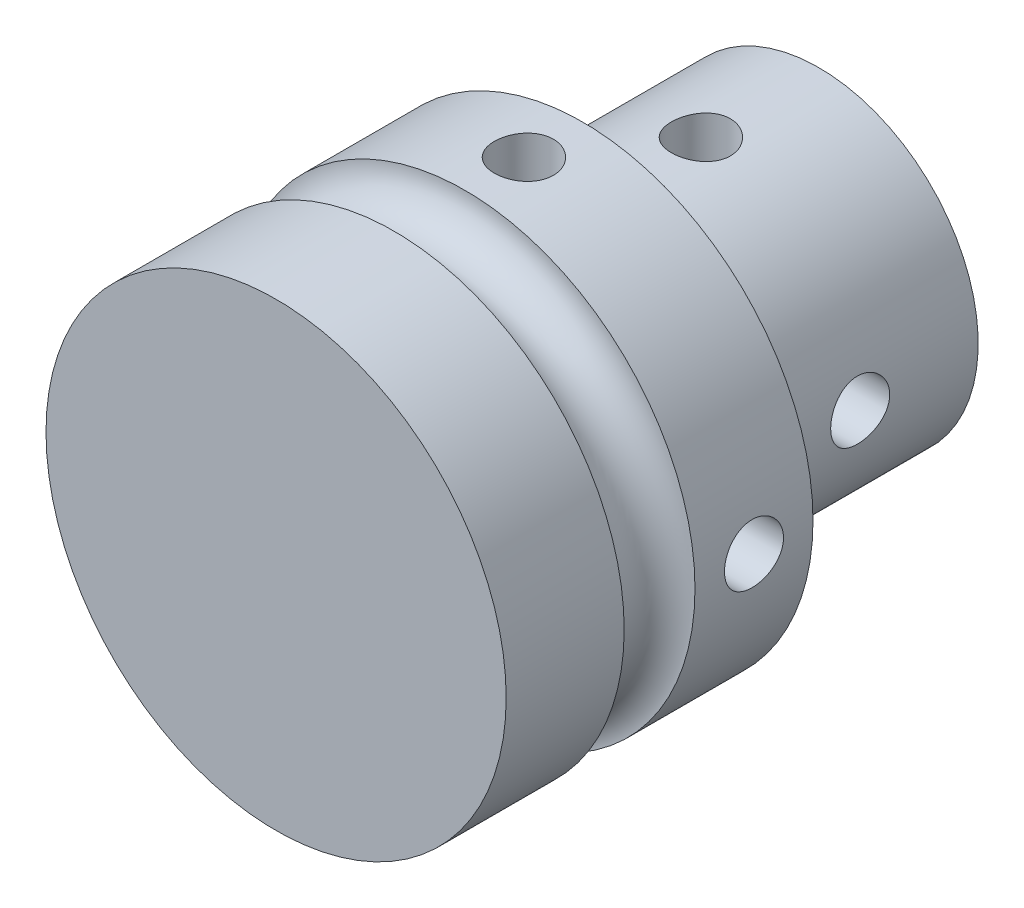
SolidWorks part; units mm, degrees
ref_plane "Plano frontal" through (0, 0, 0) normal (0, 0, 1) x (1, 0, 0)
ref_plane "Plano superior" through (0, 0, 0) normal (0, 1, 0) x (1, 0, 0)
ref_plane "Plano direito" through (0, 0, 0) normal (1, 0, 0) x (0, 0, -1)
sketch "Esboço2" plane through (0, 0, 0) normal (0, 0, 1) x (1, 0, 0)
  circle A0 centre (0, 0) radius 9.75
  dimension "D1" = 19.5
extrude "Ressalto-extrusão1" add sketch "Esboço2" along normal blind 13 contours A0
sketch "Esboço3" plane through (0, 0, 0) normal (0, 1, 0) x (1, 0, 0)
  line L0 (-9.75, -6.5) -> (9.75, -6.5) construction
  line L1 (-9.75, 0) -> (-9.75, -13) construction
  line L2 (9.75, -13) -> (9.75, 0) construction
  line L3 (0, 0) -> (0, -13) construction
  line L4 (-9.75, -13) -> (9.75, -13) construction
  circle A0 centre (9.75, -6.5) radius 1.5
  dimension "D1" = 3
revolve "Corte-Revolução1" cut sketch "Esboço3" angle 360 about L3
sketch "Esboço4" plane through (0, 0, 0) normal (0, 0, -1) x (-1, 0, 0)
  circle A0 centre (0, 0) radius 6.75
  dimension "D1" = 13.5
extrude "Ressalto-extrusão2" add sketch "Esboço4" along normal blind 10
sketch "Esboço11" plane through (0, 0, 0) normal (0, 1, 0) x (1, 0, 0)
  line L0 (0, 0) -> (0, -5) construction
  line L1 (9.75, -5) -> (-9.75, -5) construction
  circle A0 centre (0, -2.5) radius 1.5
  dimension "D1" = 3
ref_plane "Plano1" through (0, 9.75, 0) normal (0, 1, 0) x (1, 0, 0)
sketch "Esboço12" plane through (0, 9.75, 0) normal (0, 1, 0) x (1, 0, 0)
  point P0 (0, -2.5)
hole_wizard "Broca de rosquear para tarraxa de M36" positions "Esboço14" profile "Esboço15" hole size "M3" standard "ISO"
sketch "Esboço14" plane through (0, 9.75, 0) normal (0, 1, 0) x (1, 0, 0)
  point P0 (0, -2.5)
sketch "Esboço15" plane through (0, 9.75, 2.5) normal (1, 0, 0) x (0, 0, 1)
  line L0 (0, 0) -> (0, 8.7511)
  line L1 (0, 8.7511) -> (1.25, 8)
  line L2 (1.25, 8) -> (1.25, 0)
  line L5 (1.25, 0) -> (0, 0)
  line L10 (0, 8.7511) -> (-1.25, 8) construction
  line L11 (0, -6.35) -> (0, 107.95) construction
  dimension "Hole Dia." = 2.5
  dimension "Hole Depth" = 8
  dimension "Drill Angle" = 118
pattern_circular "PadrãoCircular1" count 4 over 360 about axis through (0, 0, 0) along (0, 0, 1) of "Broca de rosquear para tarraxa de M36"
ref_plane "Plano2" through (0, 6.75, 0) normal (0, 1, 0) x (1, 0, 0)
sketch "Esboço16" plane through (0, 6.75, 0) normal (0, 1, 0) x (1, 0, 0)
  line L0 (0, 10) -> (0, 0) construction
  line L1 (6.75, 10) -> (-6.75, 10) construction
  point P5 (0, 5)
hole_wizard "Broca de rosquear para tarraxa de M310" positions "Esboço18" profile "Esboço19" hole size "M3" standard "ISO"
sketch "Esboço18" plane through (0, 6.75, 0) normal (0, 1, 0) x (1, 0, 0)
  point P0 (0, 5)
sketch "Esboço19" plane through (0, 6.75, -5) normal (1, 0, 0) x (0, 0, 1)
  line L0 (0, 0) -> (0, 5.7511)
  line L1 (0, 5.7511) -> (1.25, 5)
  line L2 (1.25, 5) -> (1.25, 0)
  line L5 (1.25, 0) -> (0, 0)
  line L10 (0, 5.7511) -> (-1.25, 5) construction
  line L11 (0, -6.35) -> (0, 107.95) construction
  dimension "Hole Dia." = 2.5
  dimension "Hole Depth" = 5
  dimension "Drill Angle" = 118
pattern_circular "PadrãoCircular2" count 4 over 360 about axis through (0, 0, 0) along (0, 0, 1) of "Broca de rosquear para tarraxa de M310"
